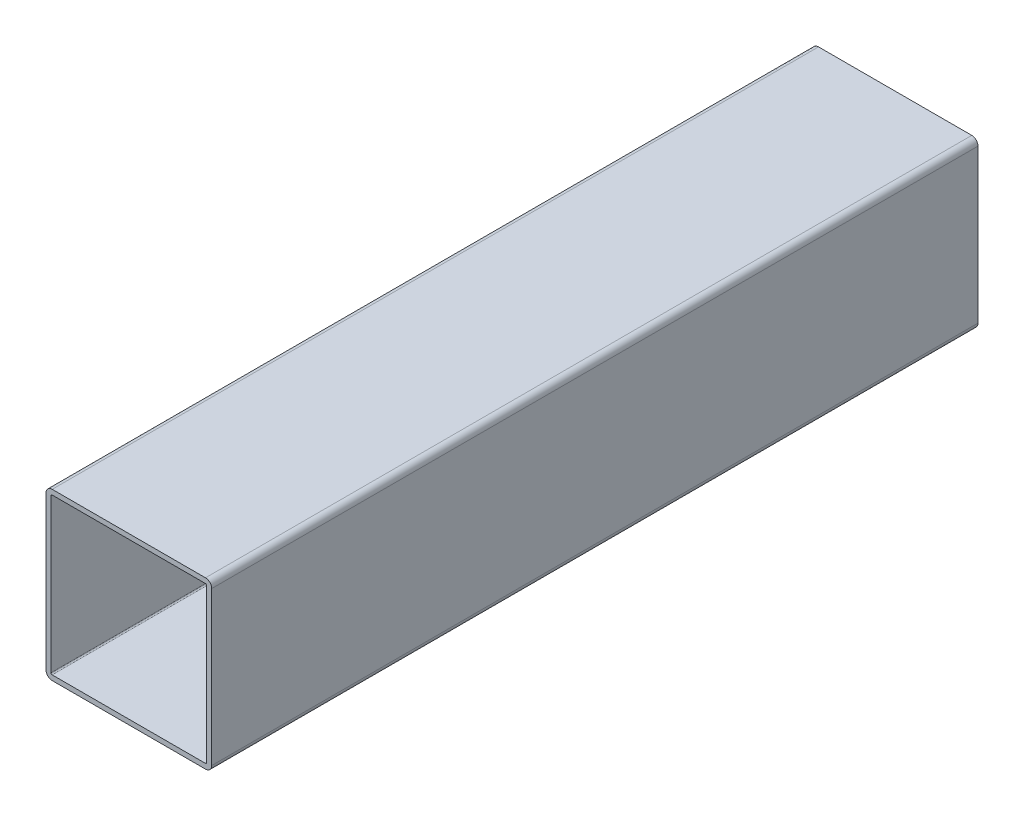
SolidWorks part; units mm, degrees
material "AISI 1020 Steel, Cold Rolled"
ref_plane "Front Plane" through (0, 0, 0) normal (0, 0, 1) x (1, 0, 0)
ref_plane "Top Plane" through (0, 0, 0) normal (0, 1, 0) x (1, 0, 0)
ref_plane "Right Plane" through (0, 0, 0) normal (1, 0, 0) x (0, 0, -1)
sketch "Sketch1" plane through (0, 0, 0) normal (0, 1, 0) x (1, 0, 0)
  line L0 (0, 0) -> (0, 185)
  dimension "D1" = 185
other "Structural Member1"
ref_plane "Plane1" through (0, 0, 0) normal (0, 0, -1) x (-1, 0, 0)
sketch "Sketch12" plane through (0, 0, 0) normal (0, 0, -1) x (-1, 0, 0)
  line L0 (-18.5, -18.8) -> (18.5, -18.8)
  line L1 (-18.8, -18.5) -> (-18.8, 18.5)
  line L2 (18.5, 18.8) -> (-18.5, 18.8)
  line L3 (18.8, 18.5) -> (18.8, -18.5)
  line L4 (-18.5, -20) -> (18.5, -20)
  line L5 (-20, -18.5) -> (-20, 18.5)
  line L6 (18.5, 20) -> (-18.5, 20)
  line L7 (20, 18.5) -> (20, -18.5)
  arc A0 (20, 18.5) -> (18.5, 20) centre (18.5, 18.5) ccw
  arc A1 (18.5, -20) -> (20, -18.5) centre (18.5, -18.5) ccw
  arc A2 (-20, -18.5) -> (-18.5, -20) centre (-18.5, -18.5) ccw
  arc A3 (-18.5, 20) -> (-20, 18.5) centre (-18.5, 18.5) ccw
  arc A4 (-18.5, 18.8) -> (-18.8, 18.5) centre (-18.5, 18.5) ccw
  arc A5 (18.8, 18.5) -> (18.5, 18.8) centre (18.5, 18.5) ccw
  arc A6 (18.5, -18.8) -> (18.8, -18.5) centre (18.5, -18.5) ccw
  arc A7 (-18.8, -18.5) -> (-18.5, -18.8) centre (-18.5, -18.5) ccw
  point P0 (-20, 0)
  point P1 (20, 0)
  point P2 (0, 20)
  point P3 (0, -20)
  point P4 (0, 0)
  point P5 (-20, -20)
  point P6 (20, -20)
  point P7 (20, 20)
  point P8 (-20, 20)
  point P33 (0, 0)
  dimension "D1" = 1.5
  dimension "Thickness" = 1.2
  dimension "V_leg" = 40
